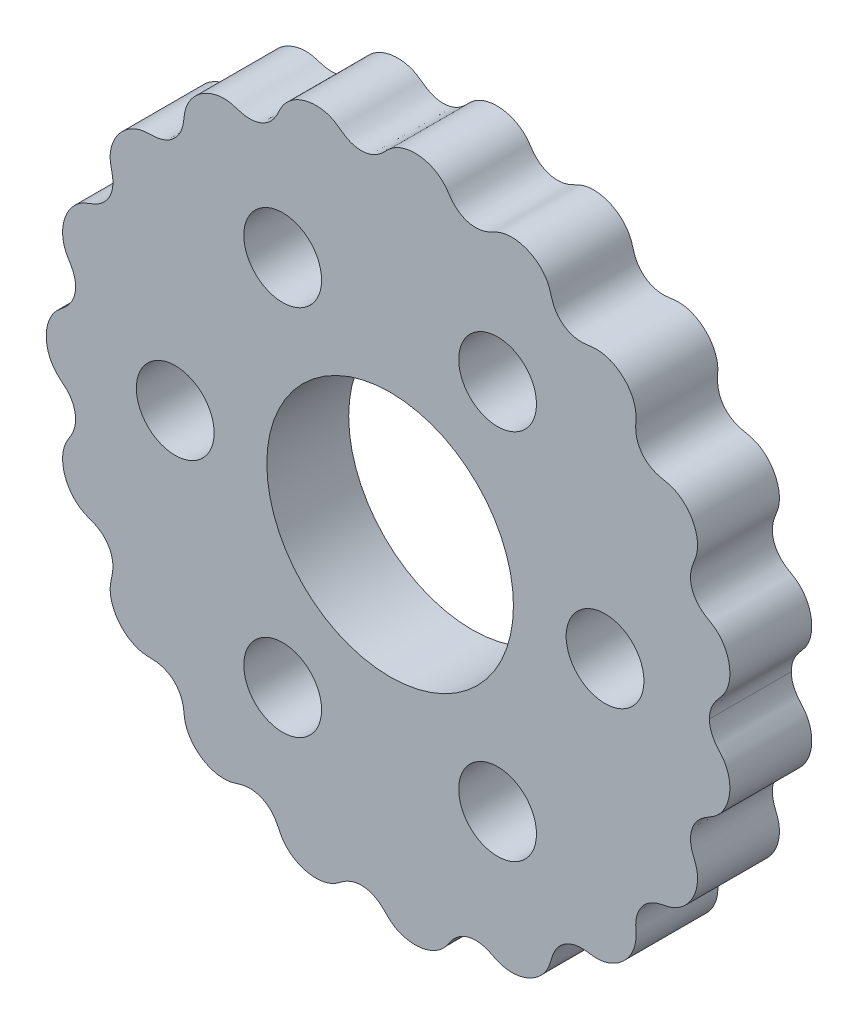
SolidWorks part; units mm, degrees
ref_plane "Front Plane" through (0, 0, 0) normal (0, 0, 1) x (1, 0, 0)
ref_plane "Top Plane" through (0, 0, 0) normal (0, 1, 0) x (1, 0, 0)
ref_plane "Right Plane" through (0, 0, 0) normal (1, 0, 0) x (0, 0, -1)
sketch "Sketch1" plane through (0, 0, 0) normal (0, 0, 1) x (1, 0, 0)
  spline S0 degree 4 poles (-31.8087, -8.3969) (-31.764, -8.2691) (-31.6639, -8.0159) (-31.4655, -7.6598) (-31.1691, -7.2053) (-30.9071, -6.6701) (-30.7339, -6.0446) (-30.7067, -5.3395) (-30.8743, -4.5991) (-31.202, -3.9751) (-31.5792, -3.5342) (-31.9195, -3.2325) (-32.1769, -3.0228) (-32.3798, -2.8514) (-32.5721, -2.6678) (-32.7498, -2.47) (-32.9141, -2.2555) (-33.0634, -2.0249) (-33.1965, -1.7798) (-33.3123, -1.5212) (-33.4088, -1.2549) (-33.486, -0.9821) (-33.5366, -0.7399) (-33.5679, -0.5287) (-33.586, -0.3554) (-33.5956, -0.2127) (-33.5998, -0.0688) (-33.6004, 0.0146) (-33.5988, 0.1031) (-33.596, 0.1833) (-33.5909, 0.283) (-33.5821, 0.3963) (-33.5677, 0.5251) (-33.5459, 0.6748) (-33.5119, 0.86) (-33.46, 1.0798) (-33.3837, 1.3324) (-33.2743, 1.6132) (-33.1433, 1.8849) (-32.9583, 2.1982) (-32.7034, 2.5408) (-32.3565, 2.8876) (-31.9193, 3.2225) (-31.4691, 3.6416) (-31.0653, 4.1903) (-30.7833, 4.8739) (-30.703, 5.5658) (-30.7675, 6.1499) (-30.9099, 6.6436) (-31.0908, 7.0584) (-31.3409, 7.4736) (-31.6179, 7.9122) (-31.8004, 8.3373) (-31.9114, 8.7239) (-31.9713, 9.0629) (-31.9997, 9.3469) (-32.0083, 9.704) (-31.9774, 10.1317) (-31.8546, 10.7734) (-31.5865, 11.4551) (-31.1931, 12.0791) (-30.6879, 12.6065) (-30.2308, 12.9526) (-29.7292, 13.2131) (-29.205, 13.3906) (-28.637, 13.6314) (-28.0674, 14.0097) (-27.5687, 14.5528) (-27.213, 15.2562) (-27.0703, 15.9587) (-27.0855, 16.6034) (-27.1978, 17.177) (-27.3255, 17.6888) (-27.3765, 18.2292) (-27.3395, 18.7827) (-27.1822, 19.4782) (-26.8215, 20.2848) (-26.2771, 20.9924) (-25.582, 21.5533) (-24.9276, 21.8898) (-24.3833, 22.0672) (-23.8295, 22.1496) (-23.2855, 22.1482) (-22.6811, 22.1886) (-22.031, 22.3526) (-21.3866, 22.6906) (-20.8163, 23.2264) (-20.4423, 23.8377) (-20.237, 24.4537) (-20.15, 25.0358) (-20.1069, 25.5648) (-19.9855, 26.0972) (-19.774, 26.6141) (-19.4018, 27.2279) (-18.7973, 27.8829) (-18.0474, 28.383) (-17.1992, 28.6923) (-16.4658, 28.7982) (-15.894, 28.7883) (-15.3483, 28.6868) (-14.8421, 28.5126) (-14.2685, 28.3555) (-13.614, 28.2953) (-12.895, 28.3955) (-12.1675, 28.7114) (-11.6001, 29.1743) (-11.1949, 29.7066) (-10.9216, 30.2391) (-10.7077, 30.7259) (-10.4141, 31.1928) (-10.0364, 31.6177) (-9.4652, 32.0835) (-8.6679, 32.4974) (-7.7968, 32.7119) (-6.9097, 32.7165) (-6.2084, 32.579) (-5.686, 32.3885) (-5.2118, 32.1222) (-4.7941, 31.7983) (-4.3116, 31.466) (-3.7247, 31.1954) (-3.0223, 31.0479) (-2.2355, 31.096) (-1.54, 31.3385) (-0.9678, 31.7102) (-0.5218, 32.1345) (-0.1488, 32.5418) (0.2918, 32.8939) (0.792, 33.1715) (1.4771, 33.4198) (2.2059, 33.5279) (2.9374, 33.4983) (3.6443, 33.3358) (4.1799, 33.13) (4.6689, 32.8545) (5.0991, 32.5156) (5.4628, 32.123) (5.7529, 31.6913) (6.0905, 31.2176) (6.5489, 30.7582) (7.3252, 30.2694) (8.2488, 30.0775) (9.117, 30.2014) (9.856, 30.5182) (10.3323, 30.7803) (10.9982, 31.0463) (11.8838, 31.174) (12.9418, 31.046) (13.9307, 30.612) (14.6576, 30.0516) (15.1407, 29.4849) (15.4412, 28.9882) (15.6456, 28.459) (15.7764, 27.9227) (15.9824, 27.3417) (16.3264, 26.7518) (16.8408, 26.2239) (17.5229, 25.8294) (18.2166, 25.6476) (18.8616, 25.6246) (19.4418, 25.7004) (19.9649, 25.7786) (20.5051, 25.7706) (21.045, 25.6778) (21.5735, 25.5006) (22.0784, 25.2462) (22.6817, 24.8284) (23.2071, 24.2932) (23.628, 23.6545) (23.8999, 22.9526) (24.0182, 22.388) (24.0372, 21.8334) (23.9901, 21.3041) (23.9921, 20.7045) (24.1144, 20.046) (24.414, 19.3815) (24.917, 18.7796) (25.5036, 18.3717) (26.0998, 18.1302) (26.6694, 18.005) (27.1881, 17.9154) (27.7016, 17.7434) (28.1918, 17.4862) (28.7631, 17.0621) (29.3551, 16.4072) (29.7829, 15.6237) (30.0158, 14.7606) (30.0593, 14.0245) (30.0013, 13.4537) (29.8516, 12.913) (29.6307, 12.4146) (29.4267, 11.8428) (29.3187, 11.1795) (29.3739, 10.4531) (29.6402, 9.7174) (30.0528, 9.1325) (30.5354, 8.7004) (31.0336, 8.3895) (31.4993, 8.1373) (31.9359, 7.8112) (32.3223, 7.4096) (32.7323, 6.8224) (33.0261, 6.1468) (33.189, 5.4238) (33.2133, 4.6814) (33.1447, 4.0835) (32.9897, 3.5196) (32.7545, 3.0032) (32.4844, 2.6023) (32.2235, 2.3017) (32.006, 2.0519) (31.8403, 1.8446) (31.6977, 1.6409) (31.5782, 1.4419) (31.4803, 1.2501) (31.4014, 1.0677) (31.3347, 0.8803) (31.2875, 0.7132) (31.2553, 0.5673) (31.234, 0.4451) (31.2203, 0.3479) (31.21, 0.2492) (31.2031, 0.1433) (31.1996, 0.0338) (31.1998, -0.0467) (31.204, -0.1606) (31.212, -0.2705) (31.2229, -0.3679) (31.2361, -0.4579) (31.2642, -0.6163) (31.3189, -0.8402) (31.4166, -1.1237) (31.596, -1.4885) (31.8407, -1.861) (32.1558, -2.2256) (32.5005, -2.6154) (32.7875, -3.0674) (33.0057, -3.5693) (33.1481, -4.1118) (33.2117, -4.6812) (33.1928, -5.321) (33.0607, -6.0164) (32.7812, -6.7409) (32.3772, -7.3595) (31.936, -7.8123) (31.5966, -8.0596) (31.419, -8.1706) (31.329, -8.2243) knots 0 0 0 0 0 0.004045 0.008089 0.012134 0.016179 0.021743 0.027308 0.032936 0.038565 0.042525 0.044505 0.046486 0.048466 0.050446 0.052427 0.054407 0.056517 0.058628 0.060738 0.062849 0.064959 0.067069 0.068124 0.06918 0.070235 0.07129 0.071851 0.072413 0.072974 0.073535 0.074658 0.075781 0.076903 0.078026 0.080271 0.082516 0.084762 0.087007 0.089252 0.093357 0.097462 0.101567 0.105672 0.111646 0.117619 0.123334 0.126191 0.129048 0.132912 0.136776 0.14064 0.144504 0.146631 0.148759 0.150886 0.153014 0.157269 0.161524 0.170306 0.174697 0.179087 0.183211 0.187335 0.191459 0.195583 0.201571 0.207559 0.213175 0.218791 0.222721 0.226652 0.230583 0.234513 0.238825 0.243136 0.251759 0.260655 0.265103 0.269551 0.273605 0.277658 0.281712 0.285766 0.291632 0.297498 0.303155 0.308812 0.312767 0.316722 0.320677 0.324632 0.328972 0.333312 0.341993 0.350998 0.355501 0.360003 0.363992 0.367981 0.37197 0.375959 0.381698 0.387437 0.393373 0.39931 0.403272 0.407233 0.411195 0.415157 0.419637 0.424118 0.433078 0.44172 0.446041 0.450362 0.454301 0.458239 0.462178 0.466117 0.471746 0.477376 0.483351 0.489327 0.493442 0.497557 0.501672 0.505787 0.510168 0.51455 0.523312 0.527577 0.531842 0.536106 0.540371 0.544244 0.548116 0.551989 0.555862 0.561588 0.567315 0.579077 0.58313 0.587182 0.591235 0.595287 0.604417 0.613547 0.622546 0.627046 0.631546 0.63566 0.639774 0.643888 0.648002 0.653988 0.659974 0.665591 0.671207 0.675147 0.679087 0.683026 0.686966 0.69117 0.695374 0.699577 0.703781 0.712976 0.717573 0.722171 0.726132 0.730093 0.734054 0.738015 0.743965 0.749914 0.755517 0.76112 0.765042 0.768964 0.772886 0.776809 0.78111 0.785412 0.794015 0.80293 0.807388 0.811846 0.815908 0.81997 0.824033 0.828095 0.833974 0.839853 0.845497 0.85114 0.855087 0.859033 0.86298 0.866927 0.871258 0.875588 0.884249 0.88872 0.893191 0.897661 0.902132 0.906085 0.910039 0.912015 0.913992 0.915969 0.917946 0.919426 0.920907 0.922388 0.923869 0.92535 0.92609 0.92683 0.927571 0.928311 0.929052 0.929792 0.930649 0.931505 0.932191 0.932877 0.933563 0.934249 0.936993 0.939736 0.94248 0.946355 0.95023 0.954105 0.95798 0.962239 0.966498 0.970757 0.975016 0.981262 0.987508 0.993754 0.996877 1 1 1 1 1 construction
  spline S1 degree 4 poles (-33.6, 0) (-33.6, 0.0162) (-33.5998, 0.0487) (-33.5988, 0.1031) (-33.596, 0.1833) (-33.5909, 0.283) (-33.5821, 0.3963) (-33.5677, 0.5251) (-33.5459, 0.6748) (-33.5119, 0.86) (-33.46, 1.0798) (-33.3837, 1.3324) (-33.2743, 1.6132) (-33.1433, 1.8849) (-32.9583, 2.1982) (-32.7034, 2.5408) (-32.3565, 2.8876) (-31.9193, 3.2225) (-31.4691, 3.6416) (-31.0653, 4.1903) (-30.7833, 4.8739) (-30.703, 5.5658) (-30.7675, 6.1499) (-30.9099, 6.6436) (-31.0908, 7.0584) (-31.3409, 7.4736) (-31.6179, 7.9122) (-31.8004, 8.3373) (-31.9114, 8.7239) (-31.9713, 9.0629) (-31.9997, 9.3469) (-32.0083, 9.704) (-31.9774, 10.1317) (-31.8546, 10.7734) (-31.5865, 11.4551) (-31.1931, 12.0791) (-30.6879, 12.6065) (-30.2308, 12.9526) (-29.7292, 13.2131) (-29.205, 13.3906) (-28.637, 13.6314) (-28.0674, 14.0097) (-27.5687, 14.5528) (-27.213, 15.2562) (-27.0703, 15.9587) (-27.0855, 16.6034) (-27.1978, 17.177) (-27.3255, 17.6888) (-27.3765, 18.2292) (-27.3395, 18.7827) (-27.1822, 19.4782) (-26.8215, 20.2848) (-26.2771, 20.9924) (-25.582, 21.5533) (-24.9276, 21.8898) (-24.3833, 22.0672) (-23.8295, 22.1496) (-23.2855, 22.1482) (-22.6811, 22.1886) (-22.031, 22.3526) (-21.3866, 22.6906) (-20.8163, 23.2264) (-20.4423, 23.8377) (-20.237, 24.4537) (-20.15, 25.0358) (-20.1069, 25.5648) (-19.9855, 26.0972) (-19.774, 26.6141) (-19.4018, 27.2279) (-18.7973, 27.8829) (-18.0474, 28.383) (-17.1992, 28.6923) (-16.4658, 28.7982) (-15.894, 28.7883) (-15.3483, 28.6868) (-14.8421, 28.5126) (-14.2685, 28.3555) (-13.614, 28.2953) (-12.895, 28.3955) (-12.1675, 28.7114) (-11.6001, 29.1743) (-11.1949, 29.7066) (-10.9216, 30.2391) (-10.7077, 30.7259) (-10.4141, 31.1928) (-10.0364, 31.6177) (-9.4652, 32.0835) (-8.6679, 32.4974) (-7.7968, 32.7119) (-6.9097, 32.7165) (-6.2084, 32.579) (-5.686, 32.3885) (-5.2118, 32.1222) (-4.7941, 31.7983) (-4.3116, 31.466) (-3.7247, 31.1954) (-3.0223, 31.0479) (-2.2355, 31.096) (-1.54, 31.3385) (-0.9678, 31.7102) (-0.5218, 32.1345) (-0.1488, 32.5418) (0.2918, 32.8939) (0.792, 33.1715) (1.4771, 33.4198) (2.2059, 33.5279) (2.9374, 33.4983) (3.6443, 33.3358) (4.1799, 33.13) (4.6689, 32.8545) (5.0991, 32.5156) (5.4628, 32.123) (5.7529, 31.6913) (6.0905, 31.2176) (6.5489, 30.7582) (7.3252, 30.2694) (8.2488, 30.0775) (9.117, 30.2014) (9.856, 30.5182) (10.3323, 30.7803) (10.9982, 31.0463) (11.8838, 31.174) (12.9418, 31.046) (13.9307, 30.612) (14.6576, 30.0516) (15.1407, 29.4849) (15.4412, 28.9882) (15.6456, 28.459) (15.7764, 27.9227) (15.9824, 27.3417) (16.3264, 26.7518) (16.8408, 26.2239) (17.5229, 25.8294) (18.2166, 25.6476) (18.8616, 25.6246) (19.4418, 25.7004) (19.9649, 25.7786) (20.5051, 25.7706) (21.045, 25.6778) (21.5735, 25.5006) (22.0784, 25.2462) (22.6817, 24.8284) (23.2071, 24.2932) (23.628, 23.6545) (23.8999, 22.9526) (24.0182, 22.388) (24.0372, 21.8334) (23.9901, 21.3041) (23.9921, 20.7045) (24.1144, 20.046) (24.414, 19.3815) (24.917, 18.7796) (25.5036, 18.3717) (26.0998, 18.1302) (26.6694, 18.005) (27.1881, 17.9154) (27.7016, 17.7434) (28.1918, 17.4862) (28.7631, 17.0621) (29.3551, 16.4072) (29.7829, 15.6237) (30.0158, 14.7606) (30.0593, 14.0245) (30.0013, 13.4537) (29.8516, 12.913) (29.6307, 12.4146) (29.4267, 11.8428) (29.3187, 11.1795) (29.3739, 10.4531) (29.6402, 9.7174) (30.0528, 9.1325) (30.5354, 8.7004) (31.0336, 8.3895) (31.4993, 8.1373) (31.9359, 7.8112) (32.3223, 7.4096) (32.7323, 6.8224) (33.0261, 6.1468) (33.189, 5.4238) (33.2133, 4.6814) (33.1447, 4.0835) (32.9897, 3.5196) (32.7545, 3.0032) (32.4844, 2.6023) (32.2235, 2.3017) (32.006, 2.0519) (31.8403, 1.8446) (31.6977, 1.6409) (31.5782, 1.4419) (31.4803, 1.2501) (31.4014, 1.0677) (31.3347, 0.8803) (31.2875, 0.7132) (31.2553, 0.5673) (31.234, 0.4451) (31.2203, 0.3479) (31.21, 0.2492) (31.2031, 0.1433) (31.2006, 0.0643) (31.2, 0.0213) (31.2, 0) knots 0.07129 0.07129 0.07129 0.07129 0.07129 0.071851 0.072413 0.072974 0.073535 0.074658 0.075781 0.076903 0.078026 0.080271 0.082516 0.084762 0.087007 0.089252 0.093357 0.097462 0.101567 0.105672 0.111646 0.117619 0.123334 0.126191 0.129048 0.132912 0.136776 0.14064 0.144504 0.146631 0.148759 0.150886 0.153014 0.157269 0.161524 0.170306 0.174697 0.179087 0.183211 0.187335 0.191459 0.195583 0.201571 0.207559 0.213175 0.218791 0.222721 0.226652 0.230583 0.234513 0.238825 0.243136 0.251759 0.260655 0.265103 0.269551 0.273605 0.277658 0.281712 0.285766 0.291632 0.297498 0.303155 0.308812 0.312767 0.316722 0.320677 0.324632 0.328972 0.333312 0.341993 0.350998 0.355501 0.360003 0.363992 0.367981 0.37197 0.375959 0.381698 0.387437 0.393373 0.39931 0.403272 0.407233 0.411195 0.415157 0.419637 0.424118 0.433078 0.44172 0.446041 0.450362 0.454301 0.458239 0.462178 0.466117 0.471746 0.477376 0.483351 0.489327 0.493442 0.497557 0.501672 0.505787 0.510168 0.51455 0.523312 0.527577 0.531842 0.536106 0.540371 0.544244 0.548116 0.551989 0.555862 0.561588 0.567315 0.579077 0.58313 0.587182 0.591235 0.595287 0.604417 0.613547 0.622546 0.627046 0.631546 0.63566 0.639774 0.643888 0.648002 0.653988 0.659974 0.665591 0.671207 0.675147 0.679087 0.683026 0.686966 0.69117 0.695374 0.699577 0.703781 0.712976 0.717573 0.722171 0.726132 0.730093 0.734054 0.738015 0.743965 0.749914 0.755517 0.76112 0.765042 0.768964 0.772886 0.776809 0.78111 0.785412 0.794015 0.80293 0.807388 0.811846 0.815908 0.81997 0.824033 0.828095 0.833974 0.839853 0.845497 0.85114 0.855087 0.859033 0.86298 0.866927 0.871258 0.875588 0.884249 0.88872 0.893191 0.897661 0.902132 0.906085 0.910039 0.912015 0.913992 0.915969 0.917946 0.919426 0.920907 0.922388 0.923869 0.92535 0.92609 0.92683 0.927571 0.928311 0.929052 0.929792 0.929792 0.929792 0.929792 0.929792
  spline S4 degree 4 poles (31.329, 8.2242) (31.4191, 8.1708) (31.5965, 8.0595) (31.936, 7.8123) (32.3771, 7.3595) (32.7813, 6.741) (33.0607, 6.0164) (33.1928, 5.321) (33.2117, 4.6812) (33.1481, 4.1118) (33.0057, 3.5693) (32.7875, 3.0674) (32.5005, 2.6154) (32.1558, 2.2256) (31.8407, 1.861) (31.596, 1.4885) (31.4166, 1.1236) (31.3113, 0.8185) (31.2537, 0.5708) (31.2255, 0.3919) (31.212, 0.2677) (31.204, 0.1559) (31.1998, 0.0482) (31.1996, -0.0352) (31.2031, -0.1393) (31.21, -0.2463) (31.2229, -0.374) (31.2451, -0.5185) (31.2808, -0.6889) (31.3347, -0.8806) (31.4014, -1.0676) (31.4803, -1.2501) (31.5782, -1.4419) (31.6977, -1.6409) (31.8403, -1.8446) (32.006, -2.0518) (32.2235, -2.3017) (32.4844, -2.6023) (32.7545, -3.0032) (32.9897, -3.5196) (33.1447, -4.0835) (33.2133, -4.6814) (33.189, -5.4238) (33.0261, -6.1468) (32.7323, -6.8224) (32.3223, -7.4096) (31.9359, -7.8112) (31.4993, -8.1373) (31.0336, -8.3895) (30.5354, -8.7004) (30.0528, -9.1325) (29.6402, -9.7174) (29.3739, -10.4531) (29.3187, -11.1795) (29.4267, -11.8428) (29.6307, -12.4146) (29.8516, -12.913) (30.0013, -13.4537) (30.0593, -14.0245) (30.0159, -14.7606) (29.7829, -15.6237) (29.3551, -16.4072) (28.7631, -17.0621) (28.1918, -17.4862) (27.7016, -17.7434) (27.1881, -17.9154) (26.6694, -18.005) (26.0998, -18.1302) (25.5036, -18.3717) (24.917, -18.7796) (24.414, -19.3815) (24.1144, -20.046) (23.9921, -20.7045) (23.9901, -21.3041) (24.0372, -21.8334) (24.0182, -22.388) (23.8999, -22.9526) (23.628, -23.6545) (23.2071, -24.2932) (22.6817, -24.8284) (22.0784, -25.2462) (21.5735, -25.5006) (21.045, -25.6778) (20.5051, -25.7706) (19.9649, -25.7786) (19.4418, -25.7004) (18.8616, -25.6246) (18.2166, -25.6476) (17.5229, -25.8294) (16.8408, -26.2239) (16.3264, -26.7518) (15.9823, -27.3417) (15.7764, -27.9227) (15.6456, -28.459) (15.4412, -28.9882) (15.1407, -29.4849) (14.6576, -30.0516) (13.9307, -30.612) (12.9418, -31.046) (11.8838, -31.174) (10.9982, -31.0463) (10.3324, -30.7803) (9.856, -30.5182) (9.117, -30.2014) (8.2488, -30.0775) (7.3252, -30.2694) (6.5489, -30.7582) (6.0905, -31.2176) (5.7529, -31.6913) (5.4628, -32.123) (5.0991, -32.5156) (4.6689, -32.8545) (4.1799, -33.13) (3.6443, -33.3358) (2.9374, -33.4983) (2.2059, -33.5279) (1.4771, -33.4198) (0.792, -33.1715) (0.2918, -32.8939) (-0.1488, -32.5418) (-0.5218, -32.1345) (-0.9678, -31.7102) (-1.54, -31.3385) (-2.2355, -31.096) (-3.0223, -31.0479) (-3.7247, -31.1954) (-4.3116, -31.466) (-4.7941, -31.7983) (-5.2118, -32.1222) (-5.686, -32.3885) (-6.2084, -32.579) (-6.9097, -32.7165) (-7.7968, -32.7119) (-8.6679, -32.4974) (-9.4652, -32.0835) (-10.0364, -31.6177) (-10.4141, -31.1928) (-10.7077, -30.7259) (-10.9216, -30.2391) (-11.1949, -29.7066) (-11.6001, -29.1743) (-12.1675, -28.7114) (-12.895, -28.3955) (-13.614, -28.2953) (-14.2685, -28.3555) (-14.8421, -28.5126) (-15.3483, -28.6868) (-15.894, -28.7883) (-16.4658, -28.7982) (-17.1992, -28.6923) (-18.0474, -28.383) (-18.7973, -27.883) (-19.4018, -27.2279) (-19.774, -26.6141) (-19.9855, -26.0972) (-20.1068, -25.5648) (-20.15, -25.0358) (-20.237, -24.4537) (-20.4423, -23.8377) (-20.8163, -23.2264) (-21.3866, -22.6906) (-22.031, -22.3526) (-22.6811, -22.1886) (-23.2855, -22.1482) (-23.8295, -22.1495) (-24.3833, -22.0673) (-24.9276, -21.8898) (-25.5819, -21.5533) (-26.2771, -20.9924) (-26.8215, -20.2848) (-27.1822, -19.4782) (-27.3395, -18.7827) (-27.3765, -18.2292) (-27.3254, -17.6888) (-27.1978, -17.177) (-27.0855, -16.6034) (-27.0703, -15.9587) (-27.213, -15.2562) (-27.5687, -14.5528) (-28.0674, -14.0097) (-28.637, -13.6314) (-29.205, -13.3906) (-29.7292, -13.2131) (-30.2308, -12.9526) (-30.6879, -12.6065) (-31.1931, -12.0791) (-31.5865, -11.4551) (-31.8546, -10.7734) (-31.9774, -10.1317) (-32.0083, -9.704) (-31.9997, -9.3469) (-31.9713, -9.0629) (-31.9114, -8.7239) (-31.8004, -8.3373) (-31.6179, -7.9122) (-31.341, -7.4736) (-31.0908, -7.0584) (-30.9099, -6.6436) (-30.7675, -6.1499) (-30.703, -5.5658) (-30.7833, -4.8739) (-31.0653, -4.1903) (-31.4691, -3.6416) (-31.9194, -3.2225) (-32.3565, -2.8876) (-32.7034, -2.5408) (-32.9584, -2.1982) (-33.1433, -1.8848) (-33.2743, -1.6133) (-33.3836, -1.3323) (-33.46, -1.0799) (-33.5118, -0.8599) (-33.5459, -0.6743) (-33.5677, -0.5264) (-33.5821, -0.3973) (-33.5909, -0.2797) (-33.597, -0.1589) (-33.6004, -0.044) (-33.6005, 0.0506) (-33.5944, 0.2439) (-33.5775, 0.4644) (-33.5438, 0.7019) (-33.486, 0.9837) (-33.4088, 1.2541) (-33.3123, 1.5215) (-33.1965, 1.7797) (-33.0317, 2.0835) (-32.8391, 2.3653) (-32.6202, 2.622) (-32.3798, 2.8513) (-32.1769, 3.0228) (-31.9195, 3.2325) (-31.5792, 3.5342) (-31.202, 3.9751) (-30.8743, 4.5991) (-30.7067, 5.3395) (-30.7338, 6.0446) (-30.9071, 6.6701) (-31.169, 7.2053) (-31.4655, 7.6597) (-31.6639, 8.016) (-31.7641, 8.269) (-31.8086, 8.397) knots 0 0 0 0 0 0.003123 0.006246 0.012492 0.018738 0.024984 0.029243 0.033502 0.037761 0.04202 0.045895 0.04977 0.053645 0.05752 0.060264 0.063007 0.065751 0.067123 0.067809 0.068495 0.069351 0.070208 0.070948 0.071689 0.072429 0.07317 0.07465 0.076131 0.077612 0.079093 0.080574 0.082054 0.084031 0.086008 0.087985 0.089961 0.093915 0.097868 0.102339 0.106809 0.11128 0.115751 0.124412 0.128742 0.133073 0.13702 0.140967 0.144913 0.14886 0.154503 0.160147 0.166026 0.171905 0.175967 0.18003 0.184092 0.188154 0.192612 0.19707 0.205985 0.214588 0.21889 0.223191 0.227114 0.231036 0.234958 0.23888 0.244483 0.250086 0.256035 0.261985 0.265946 0.269907 0.273868 0.277829 0.282427 0.287024 0.296219 0.300423 0.304626 0.30883 0.313034 0.316974 0.320913 0.324853 0.328793 0.334409 0.340026 0.346012 0.351998 0.356112 0.360226 0.36434 0.368454 0.372954 0.377454 0.386453 0.395583 0.404713 0.408765 0.412818 0.41687 0.420923 0.432685 0.438412 0.444138 0.448011 0.451884 0.455756 0.459629 0.463894 0.468158 0.472423 0.476688 0.48545 0.489832 0.494213 0.498328 0.502443 0.506558 0.510673 0.516649 0.522624 0.528254 0.533883 0.537822 0.541761 0.545699 0.549638 0.553959 0.55828 0.566922 0.575882 0.580363 0.584843 0.588805 0.592767 0.596728 0.60069 0.606627 0.612563 0.618302 0.624041 0.62803 0.632019 0.636008 0.639997 0.644499 0.649002 0.658007 0.666688 0.671028 0.675368 0.679323 0.683278 0.687233 0.691188 0.696845 0.702502 0.708368 0.714234 0.718288 0.722342 0.726395 0.730449 0.734897 0.739345 0.748241 0.756864 0.761175 0.765487 0.769417 0.773348 0.777279 0.781209 0.786825 0.792441 0.798429 0.804417 0.808541 0.812665 0.816789 0.820913 0.825303 0.829694 0.838476 0.842731 0.846986 0.849114 0.851241 0.853369 0.855496 0.85936 0.863224 0.867088 0.870952 0.873809 0.876666 0.882381 0.888354 0.894328 0.898433 0.902538 0.906643 0.910748 0.912993 0.915238 0.917484 0.919729 0.921974 0.923097 0.924219 0.925342 0.926465 0.927026 0.927587 0.92871 0.929765 0.93082 0.932931 0.935041 0.937151 0.939262 0.941372 0.943483 0.945593 0.949554 0.951534 0.953514 0.955495 0.957475 0.961435 0.967064 0.972692 0.978257 0.983821 0.987866 0.991911 0.995955 1 1 1 1 1 construction
  spline S5 degree 4 poles (31.2, 0) (31.2, -0.0213) (31.2006, -0.0642) (31.2031, -0.1393) (31.21, -0.2463) (31.2229, -0.374) (31.2451, -0.5185) (31.2808, -0.6889) (31.3347, -0.8806) (31.4014, -1.0676) (31.4803, -1.2501) (31.5782, -1.4419) (31.6977, -1.6409) (31.8403, -1.8446) (32.006, -2.0518) (32.2235, -2.3017) (32.4844, -2.6023) (32.7545, -3.0032) (32.9897, -3.5196) (33.1447, -4.0835) (33.2133, -4.6814) (33.189, -5.4238) (33.0261, -6.1468) (32.7323, -6.8224) (32.3223, -7.4096) (31.9359, -7.8112) (31.4993, -8.1373) (31.0336, -8.3895) (30.5354, -8.7004) (30.0528, -9.1325) (29.6402, -9.7174) (29.3739, -10.4531) (29.3187, -11.1795) (29.4267, -11.8428) (29.6307, -12.4146) (29.8516, -12.913) (30.0013, -13.4537) (30.0593, -14.0245) (30.0159, -14.7606) (29.7829, -15.6237) (29.3551, -16.4072) (28.7631, -17.0621) (28.1918, -17.4862) (27.7016, -17.7434) (27.1881, -17.9154) (26.6694, -18.005) (26.0998, -18.1302) (25.5036, -18.3717) (24.917, -18.7796) (24.414, -19.3815) (24.1144, -20.046) (23.9921, -20.7045) (23.9901, -21.3041) (24.0372, -21.8334) (24.0182, -22.388) (23.8999, -22.9526) (23.628, -23.6545) (23.2071, -24.2932) (22.6817, -24.8284) (22.0784, -25.2462) (21.5735, -25.5006) (21.045, -25.6778) (20.5051, -25.7706) (19.9649, -25.7786) (19.4418, -25.7004) (18.8616, -25.6246) (18.2166, -25.6476) (17.5229, -25.8294) (16.8408, -26.2239) (16.3264, -26.7518) (15.9823, -27.3417) (15.7764, -27.9227) (15.6456, -28.459) (15.4412, -28.9882) (15.1407, -29.4849) (14.6576, -30.0516) (13.9307, -30.612) (12.9418, -31.046) (11.8838, -31.174) (10.9982, -31.0463) (10.3324, -30.7803) (9.856, -30.5182) (9.117, -30.2014) (8.2488, -30.0775) (7.3252, -30.2694) (6.5489, -30.7582) (6.0905, -31.2176) (5.7529, -31.6913) (5.4628, -32.123) (5.0991, -32.5156) (4.6689, -32.8545) (4.1799, -33.13) (3.6443, -33.3358) (2.9374, -33.4983) (2.2059, -33.5279) (1.4771, -33.4198) (0.792, -33.1715) (0.2918, -32.8939) (-0.1488, -32.5418) (-0.5218, -32.1345) (-0.9678, -31.7102) (-1.54, -31.3385) (-2.2355, -31.096) (-3.0223, -31.0479) (-3.7247, -31.1954) (-4.3116, -31.466) (-4.7941, -31.7983) (-5.2118, -32.1222) (-5.686, -32.3885) (-6.2084, -32.579) (-6.9097, -32.7165) (-7.7968, -32.7119) (-8.6679, -32.4974) (-9.4652, -32.0835) (-10.0364, -31.6177) (-10.4141, -31.1928) (-10.7077, -30.7259) (-10.9216, -30.2391) (-11.1949, -29.7066) (-11.6001, -29.1743) (-12.1675, -28.7114) (-12.895, -28.3955) (-13.614, -28.2953) (-14.2685, -28.3555) (-14.8421, -28.5126) (-15.3483, -28.6868) (-15.894, -28.7883) (-16.4658, -28.7982) (-17.1992, -28.6923) (-18.0474, -28.383) (-18.7973, -27.883) (-19.4018, -27.2279) (-19.774, -26.6141) (-19.9855, -26.0972) (-20.1068, -25.5648) (-20.15, -25.0358) (-20.237, -24.4537) (-20.4423, -23.8377) (-20.8163, -23.2264) (-21.3866, -22.6906) (-22.031, -22.3526) (-22.6811, -22.1886) (-23.2855, -22.1482) (-23.8295, -22.1495) (-24.3833, -22.0673) (-24.9276, -21.8898) (-25.5819, -21.5533) (-26.2771, -20.9924) (-26.8215, -20.2848) (-27.1822, -19.4782) (-27.3395, -18.7827) (-27.3765, -18.2292) (-27.3254, -17.6888) (-27.1978, -17.177) (-27.0855, -16.6034) (-27.0703, -15.9587) (-27.213, -15.2562) (-27.5687, -14.5528) (-28.0674, -14.0097) (-28.637, -13.6314) (-29.205, -13.3906) (-29.7292, -13.2131) (-30.2308, -12.9526) (-30.6879, -12.6065) (-31.1931, -12.0791) (-31.5865, -11.4551) (-31.8546, -10.7734) (-31.9774, -10.1317) (-32.0083, -9.704) (-31.9997, -9.3469) (-31.9713, -9.0629) (-31.9114, -8.7239) (-31.8004, -8.3373) (-31.6179, -7.9122) (-31.341, -7.4736) (-31.0908, -7.0584) (-30.9099, -6.6436) (-30.7675, -6.1499) (-30.703, -5.5658) (-30.7833, -4.8739) (-31.0653, -4.1903) (-31.4691, -3.6416) (-31.9194, -3.2225) (-32.3565, -2.8876) (-32.7034, -2.5408) (-32.9584, -2.1982) (-33.1433, -1.8848) (-33.2743, -1.6133) (-33.3836, -1.3323) (-33.46, -1.0799) (-33.5118, -0.8599) (-33.5459, -0.6743) (-33.5677, -0.5264) (-33.5821, -0.3973) (-33.5909, -0.2797) (-33.597, -0.1589) (-33.5993, -0.0807) (-33.6, -0.0323) (-33.6, 0) knots 0.070208 0.070208 0.070208 0.070208 0.070208 0.070948 0.071689 0.072429 0.07317 0.07465 0.076131 0.077612 0.079093 0.080574 0.082054 0.084031 0.086008 0.087985 0.089961 0.093915 0.097868 0.102339 0.106809 0.11128 0.115751 0.124412 0.128742 0.133073 0.13702 0.140967 0.144913 0.14886 0.154503 0.160147 0.166026 0.171905 0.175967 0.18003 0.184092 0.188154 0.192612 0.19707 0.205985 0.214588 0.21889 0.223191 0.227114 0.231036 0.234958 0.23888 0.244483 0.250086 0.256035 0.261985 0.265946 0.269907 0.273868 0.277829 0.282427 0.287024 0.296219 0.300423 0.304626 0.30883 0.313034 0.316974 0.320913 0.324853 0.328793 0.334409 0.340026 0.346012 0.351998 0.356112 0.360226 0.36434 0.368454 0.372954 0.377454 0.386453 0.395583 0.404713 0.408765 0.412818 0.41687 0.420923 0.432685 0.438412 0.444138 0.448011 0.451884 0.455756 0.459629 0.463894 0.468158 0.472423 0.476688 0.48545 0.489832 0.494213 0.498328 0.502443 0.506558 0.510673 0.516649 0.522624 0.528254 0.533883 0.537822 0.541761 0.545699 0.549638 0.553959 0.55828 0.566922 0.575882 0.580363 0.584843 0.588805 0.592767 0.596728 0.60069 0.606627 0.612563 0.618302 0.624041 0.62803 0.632019 0.636008 0.639997 0.644499 0.649002 0.658007 0.666688 0.671028 0.675368 0.679323 0.683278 0.687233 0.691188 0.696845 0.702502 0.708368 0.714234 0.718288 0.722342 0.726395 0.730449 0.734897 0.739345 0.748241 0.756864 0.761175 0.765487 0.769417 0.773348 0.777279 0.781209 0.786825 0.792441 0.798429 0.804417 0.808541 0.812665 0.816789 0.820913 0.825303 0.829694 0.838476 0.842731 0.846986 0.849114 0.851241 0.853369 0.855496 0.85936 0.863224 0.867088 0.870952 0.873809 0.876666 0.882381 0.888354 0.894328 0.898433 0.902538 0.906643 0.910748 0.912993 0.915238 0.917484 0.919729 0.921974 0.923097 0.924219 0.925342 0.926465 0.927026 0.927587 0.92871 0.92871 0.92871 0.92871 0.92871
  point P0 (-139.8509, 41.389)
extrude "Disc profile" add sketch "Sketch1" along normal blind 8
sketch "Sketch2" plane through (0, 0, 8) normal (0, 0, 1) x (1, 0, 0)
  circle A0 centre (0, 0) radius 12.05
  circle A1 centre (-21, 0) radius 3.8
  circle A2 centre (-10.5, 18.1865) radius 3.8
  circle A3 centre (10.5, 18.1865) radius 3.8
  circle A4 centre (21, 0) radius 3.8
  circle A5 centre (10.5, -18.1865) radius 3.8
  circle A6 centre (-10.5, -18.1865) radius 3.8
  point P18 (0, 0)
  dimension "D1" = 24.1
  dimension "D3" = 7.6
  dimension "D2" = 21
  dimension "D4" = 6
extrude "Cut-Extrude2" cut sketch "Sketch2" against normal through all
